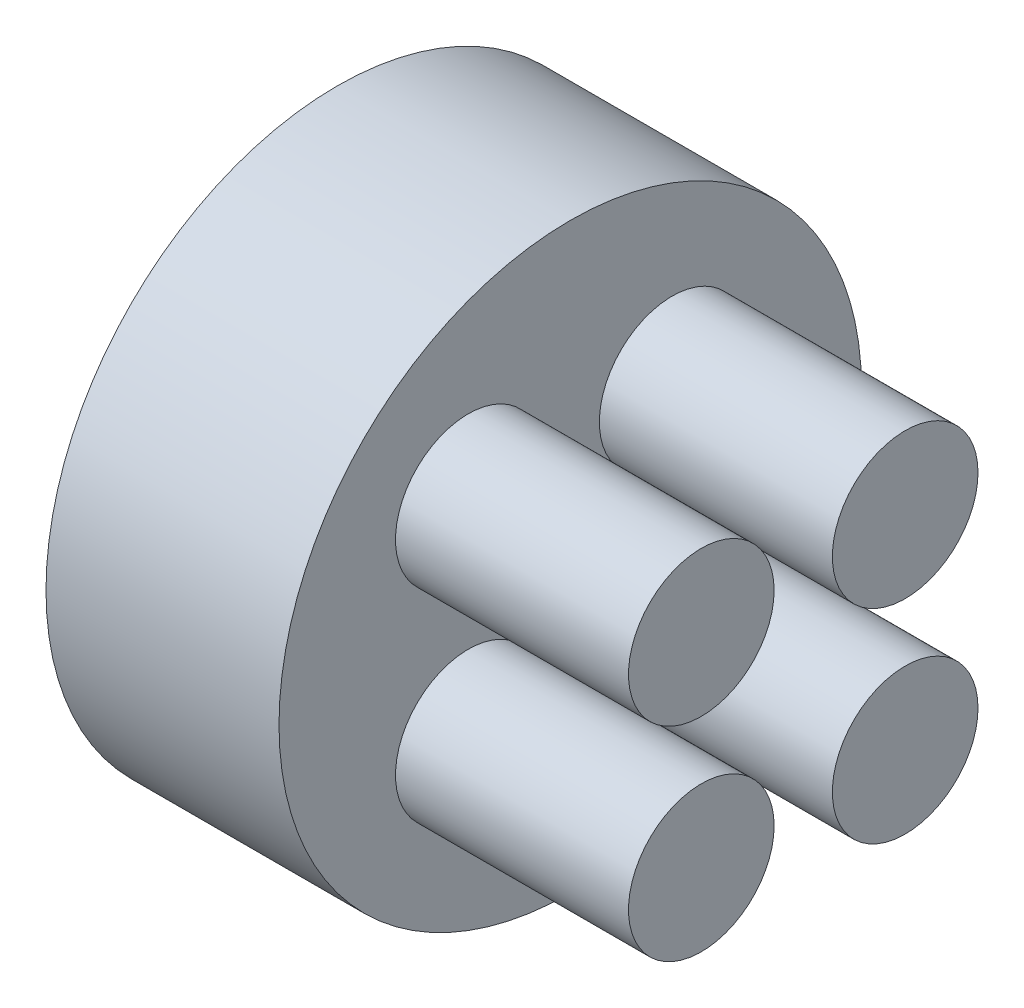
SolidWorks part; units mm, degrees
ref_plane "Спереди" through (0, 0, 0) normal (0, 0, 1) x (1, 0, 0)
ref_plane "Сверху" through (0, 0, 0) normal (0, 1, 0) x (1, 0, 0)
ref_plane "Справа" through (0, 0, 0) normal (1, 0, 0) x (0, 0, -1)
sketch "Эскиз1" plane through (0, 0, 0) normal (1, 0, 0) x (0, 0, -1)
  circle A0 centre (0, 0) radius 10
  dimension "D1" = 20
extrude "Бобышка-Вытянуть1" add sketch "Эскиз1" along normal blind 8
sketch "Эскиз2" plane through (8, 0, 0) normal (1, 0, 0) x (0, 0, -1)
  line L0 (0, 7.7083) -> (0, -6.6207) construction
  line L1 (-12.7248, 0) -> (9.8699, 0) construction
  circle A0 centre (-3.5, 3.5) radius 2.5
  circle A1 centre (3.5, 3.5) radius 2.5
  circle A2 centre (-3.5, -3.5) radius 2.5
  circle A3 centre (3.5, -3.5) radius 2.5
  dimension "D1" = 5
  dimension "D4" = 5
  dimension "D5" = 5
  dimension "D6" = 5
  dimension "D2" = 7
  dimension "D3" = 7
extrude "Бобышка-Вытянуть2" add sketch "Эскиз2" along normal blind 8
sketch "Эскиз3" plane through (0, 0, 0) normal (-1, 0, 0) x (0, 0, 1)
  circle A0 centre (0, 0) radius 2.9
  dimension "D1" = 5.8
extrude "Вырез-Вытянуть1" cut sketch "Эскиз3" against normal blind 3.5
